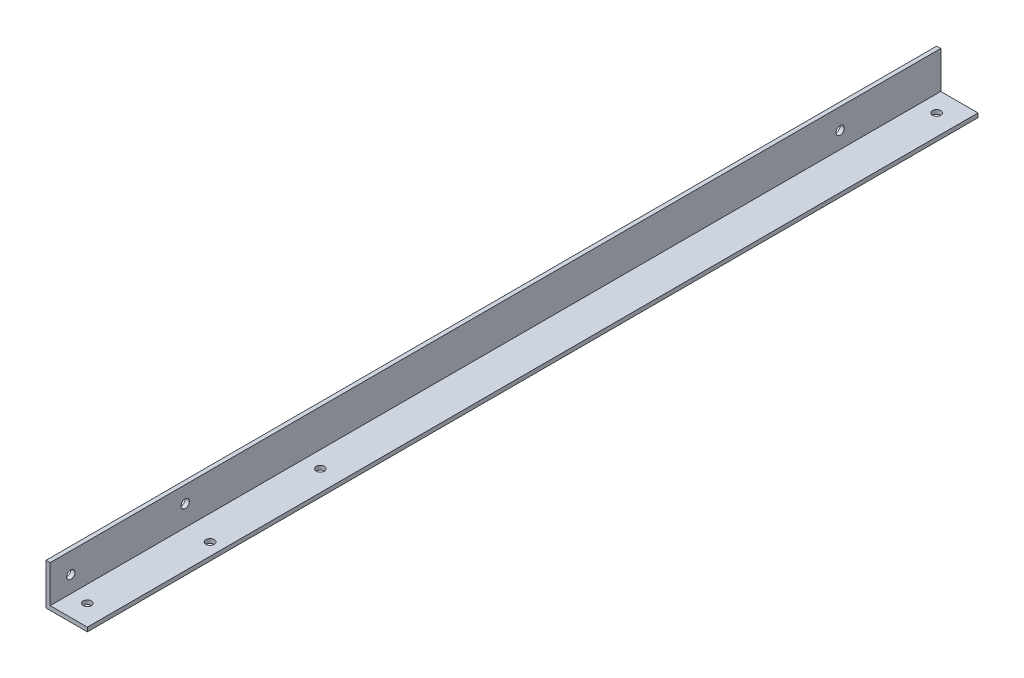
SolidWorks part; units mm, degrees
ref_plane "Plan de face" through (0, 0, 0) normal (0, 0, 1) x (1, 0, 0)
ref_plane "Plan de dessus" through (0, 0, 0) normal (0, 1, 0) x (1, 0, 0)
ref_plane "Plan de droite" through (0, 0, 0) normal (1, 0, 0) x (0, 0, -1)
sketch "Esquisse1" plane through (0, 0, 0) normal (0, 0, 1) x (1, 0, 0)
  line L0 (-20.6134, 2.046) -> (-20.6134, -12.954)
  line L1 (-20.6134, -12.954) -> (-5.6134, -12.954)
  line L2 (-5.6134, -12.954) -> (-5.6134, -11.454)
  line L3 (-5.6134, -11.454) -> (-19.1134, -11.454)
  line L4 (-19.1134, -11.454) -> (-19.1134, 2.046)
  line L5 (-19.1134, 2.046) -> (-20.6134, 2.046)
  dimension "D1" = 1.5
  dimension "D2" = 1.5
  dimension "D3" = 15
  dimension "D4" = 15
extrude "Extrusion1" add sketch "Esquisse1" along normal blind 323
sketch "Esquisse2" plane through (0, -11.454, 0) normal (0, 1, 0) x (-1, 0, 0)
  line L0 (13.1134, 7.5) -> (13.1134, 281) construction
  line L1 (5.6134, 323) -> (5.6134, 0) construction
  line L2 (5.6134, 323) -> (5.6134, 0) construction
  line L3 (5.6134, 0) -> (19.1134, 0) construction
  line L4 (19.1134, 323) -> (19.1134, 0) construction
  line L5 (5.6134, 323) -> (19.1134, 323) construction
  line L6 (20.6134, 323) -> (5.6134, 323) construction
  circle A0 centre (13.1134, 7.5) radius 1.5
  circle A1 centre (10.1134, 274) radius 1.5
  circle A2 centre (13.1134, 315.5) radius 1.5
  circle A3 centre (13.1134, 231) radius 1.5
  dimension "D1" = 7.5
  dimension "D2" = 274
  dimension "D4" = 9
  dimension "D5" = 7.5
  dimension "D7" = 7.5
  dimension "D3" = 7.5
  dimension "D6" = 7.5
  dimension "D8" = 92
extrude "Extrusion2" cut sketch "Esquisse2" against normal blind 248
sketch "Esquisse3" plane through (-19.1134, 0, 0) normal (1, 0, 0) x (0, 0, -1)
  line L0 (-36.5, -5.454) -> (-240.5, -5.454) construction
  line L1 (-323, 2.046) -> (0, 2.046) construction
  line L2 (0, -11.454) -> (0, 2.046) construction
  line L3 (0, 2.046) -> (0, -12.954) construction
  line L4 (-323, -11.454) -> (0, -11.454) construction
  line L6 (-323, -11.454) -> (-323, 2.046) construction
  circle A0 centre (-36.5, -5.454) radius 1.5
  circle A1 centre (-274, -3.954) radius 1.5
  circle A2 centre (-315.5, -5.454) radius 1.5
  point P8 (0, -5.454)
  dimension "D1" = 7.5
  dimension "D4" = 274
  dimension "D5" = 7.5
  dimension "D2" = 7.5
  dimension "D3" = 36.5
  dimension "D6" = 7.5
extrude "Extrusion3" cut sketch "Esquisse3" against normal blind 248
